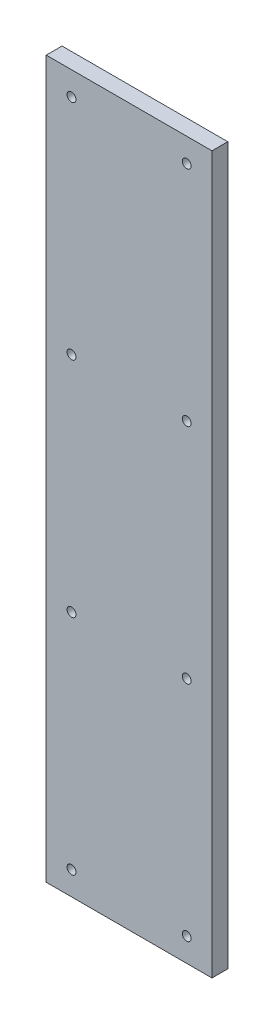
SolidWorks part; units mm, degrees
ref_plane "Front Plane" through (0, 0, 0) normal (0, 0, 1) x (1, 0, 0)
ref_plane "Top Plane" through (0, 0, 0) normal (0, 1, 0) x (1, 0, 0)
ref_plane "Right Plane" through (0, 0, 0) normal (1, 0, 0) x (0, 0, -1)
sketch "Sketch2" plane through (0, 0, 0) normal (0, 0, 1) x (1, 0, 0)
  line B0 (0, -288.29) -> (66.7, -288.29)
  line B1 (66.7, -288.29) -> (66.7, 0)
  line B2 (66.7, 0) -> (0, 0)
  line B3 (0, 0) -> (0, -288.29)
  circle B4 centre (10.175, -9.525) radius 1.7859
  circle B5 centre (56.525, -9.525) radius 1.7859
  circle B6 centre (56.525, -99.2717) radius 1.7859
  circle B7 centre (10.175, -99.2717) radius 1.7859
  circle B8 centre (10.175, -278.765) radius 1.7859
  circle B9 centre (56.525, -278.765) radius 1.7859
  circle B10 centre (10.175, -189.0183) radius 1.7859
  circle B11 centre (56.525, -189.0183) radius 1.7859
sketch_block_instance "Top_IC-1"
sketch_block "Block2" parameters "D5"=3.5719, "D1"=9.525, "D2"=9.525, "D3"=10.175, "D4"=10.175
extrude "Boss-Extrude2" add sketch "Sketch2" along normal blind 6.35
